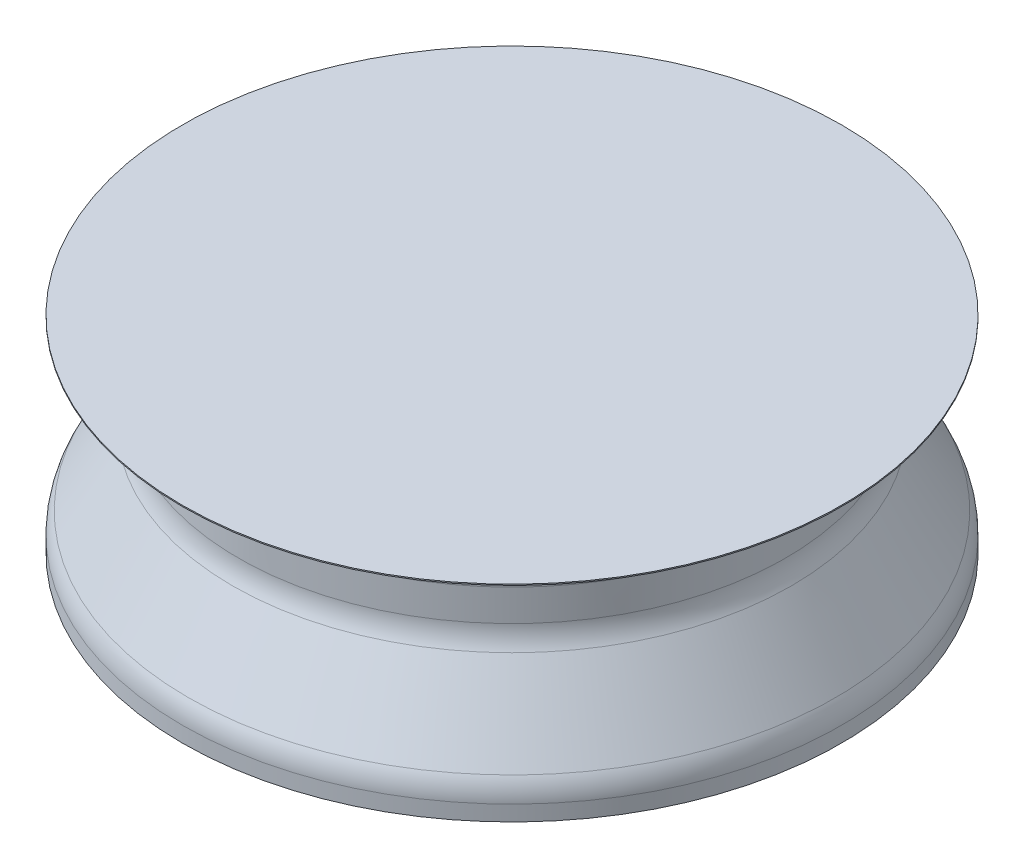
SolidWorks part; units mm, degrees
material "ABS"
ref_plane "Front Plane" through (0, 0, 0) normal (0, 0, 1) x (1, 0, 0)
ref_plane "Top Plane" through (0, 0, 0) normal (0, 1, 0) x (1, 0, 0)
ref_plane "Right Plane" through (0, 0, 0) normal (1, 0, 0) x (0, 0, -1)
sketch "Sketch1" plane through (0, 0, 0) normal (0, 0, 1) x (1, 0, 0)
  line L0 (0, 0) -> (160, 0)
  line L4 (120, 50) -> (0, 50)
  line L5 (0, 50) -> (0, 0)
sketch "Sketch3" plane through (0, 0, 0) normal (0, 1, 0) x (1, 0, 0)
  line L0 (0, 0) -> (80, 0)
  circle A0 centre (80, 0) radius 80
  circle A1 centre (80, 0) radius 88.8311
sketch "Sketch12" plane through (0, 0, 0) normal (0, 1, 0) x (1, 0, 0)
  line L0 (0, 0) -> (80, 0) construction
  circle A0 centre (80, 0) radius 80
extrude "Boss-Extrude1" add sketch "Sketch12" along normal blind 50
sketch "Sketch13" plane through (0, 0, 0) normal (0, -1, 0) x (1, 0, 0)
  circle A0 centre (80, 0) radius 25
extrude "Cut-Extrude2" cut sketch "Sketch13" against normal blind 30 contours A0
sketch "Sketch14" plane through (0, 0, 0) normal (0, 0, 1) x (1, 0, 0)
  line L13 (80, 0) -> (80, 113.3103)
  line L32 (-7.1321, 6.5115) -> (0, 6.5115)
  line L33 (-7.1321, 49.724) -> (13.6186, 49.724)
  line L34 (-7.1321, 49.724) -> (-7.1321, 6.5115)
  line L35 (-7.1321, 6.5115) -> (0, 6.5115)
  line L36 (13.6186, 49.724) -> (13.6186, 29.3169)
  line L37 (0, 50) -> (0, 0) construction
  line L38 (0, 6.5115) -> (13.6186, 29.3169)
sketch "Sketch15" plane through (0, 0, 0) normal (0, 0, 1) x (1, 0, 0)
  line L1 (0, 0) -> (160, 0) construction
  line L2 (80, 0) -> (80, 79.4287)
revolve "Cut-Revolve1" cut sketch "Sketch14" angle 360 about L13
fillet "Fillet1" radius 10 1 edges at (80, 49.724, -66.3814)
fillet "Fillet3" radius 10 1 edges at (80, 6.5115, -80)
fillet "Fillet4" radius 10 1 edges at (80, 29.3169, -66.3814)
